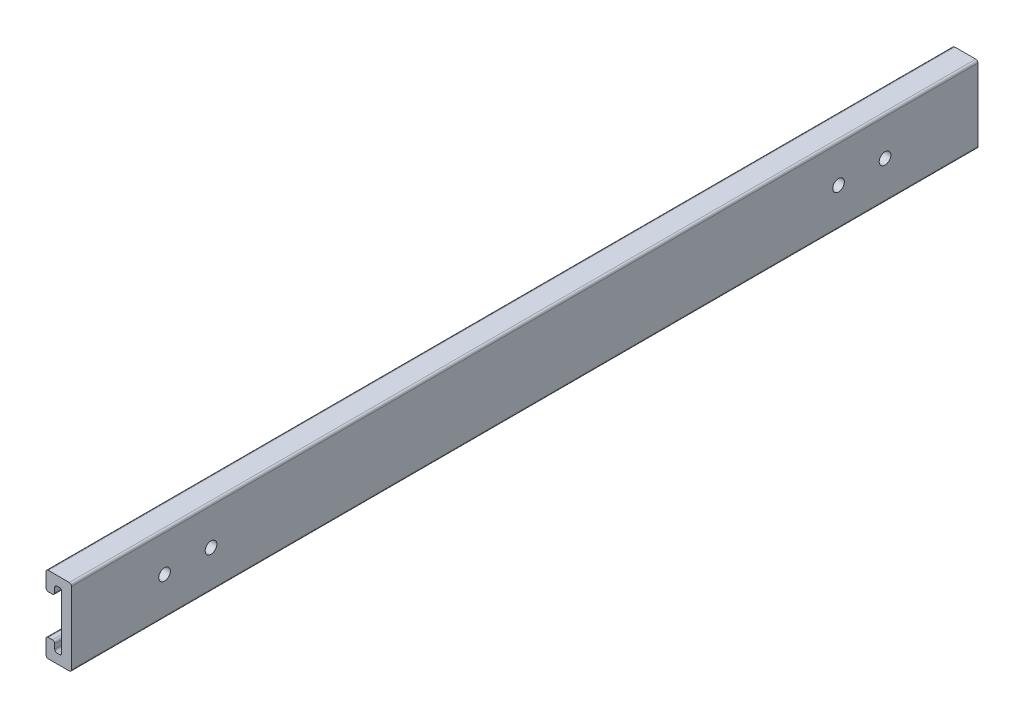
SolidWorks part; units mm, degrees
material "Brass"
ref_plane "Front Plane" through (0, 0, 0) normal (0, 0, 1) x (1, 0, 0)
ref_plane "Top Plane" through (0, 0, 0) normal (0, 1, 0) x (1, 0, 0)
ref_plane "Right Plane" through (0, 0, 0) normal (1, 0, 0) x (0, 0, -1)
sketch "Sketch1" plane through (0, 0, 0) normal (0, 0, 1) x (1, 0, 0)
  line L0 (5.5, 0) -> (-5.5, 0) construction
  line L1 (5.5, -15.5) -> (5.5, 15.5)
  line L2 (4.5, 16.5) -> (-4.5, 16.5)
  line L3 (-5.5, 15.5) -> (-5.5, 9.5)
  line L4 (-4.5, 8.5) -> (-2.75, 8.5)
  line L5 (-1.75, 9.5) -> (-1.75, 11.5)
  line L6 (-0.75, 12.5) -> (0.25, 12.5)
  line L7 (1.25, 11.5) -> (1.25, -11.5)
  line L8 (-0.75, -12.5) -> (0.25, -12.5)
  line L9 (-1.75, -9.5) -> (-1.75, -11.5)
  line L10 (-4.5, -8.5) -> (-2.75, -8.5)
  line L11 (-5.5, -15.5) -> (-5.5, -9.5)
  line L12 (4.5, -16.5) -> (-4.5, -16.5)
  arc A0 (5.5, 15.5) -> (4.5, 16.5) centre (4.5, 15.5) ccw
  arc A1 (-4.5, 16.5) -> (-5.5, 15.5) centre (-4.5, 15.5) ccw
  arc A2 (0.25, 12.5) -> (1.25, 11.5) centre (0.25, 11.5) cw
  arc A3 (-1.75, 11.5) -> (-0.75, 12.5) centre (-0.75, 11.5) cw
  arc A4 (-2.75, 8.5) -> (-1.75, 9.5) centre (-2.75, 9.5) ccw
  arc A5 (-5.5, 9.5) -> (-4.5, 8.5) centre (-4.5, 9.5) ccw
  arc A6 (-5.5, -9.5) -> (-4.5, -8.5) centre (-4.5, -9.5) cw
  arc A7 (-2.75, -8.5) -> (-1.75, -9.5) centre (-2.75, -9.5) cw
  arc A8 (-1.75, -11.5) -> (-0.75, -12.5) centre (-0.75, -11.5) ccw
  arc A9 (0.25, -12.5) -> (1.25, -11.5) centre (0.25, -11.5) ccw
  arc A10 (-4.5, -16.5) -> (-5.5, -15.5) centre (-4.5, -15.5) cw
  arc A11 (5.5, -15.5) -> (4.5, -16.5) centre (4.5, -15.5) cw
  point P4 (0, 0)
  point P11 (-5.5, -8.5)
  point P13 (5.5, 16.5)
  point P16 (-5.5, 16.5)
  point P19 (1.25, 12.5)
  point P22 (-1.75, 12.5)
  point P27 (-5.5, 8.5)
  point P46 (1.25, 0)
  point P47 (-1.75, -12.5)
  point P48 (1.25, -12.5)
  point P49 (-5.5, -16.5)
  point P50 (5.5, -16.5)
  dimension "D8" = 1
  dimension "D1" = 11
  dimension "D2" = 11
  dimension "D3" = 8
  dimension "D4" = 12.5
  dimension "D5" = 16.5
  dimension "D6" = 4.25
  dimension "D7" = 3
extrude "Boss-Extrude1" add sketch "Sketch1" along normal mid plane 390
sketch "Sketch2" plane through (1.25, 0, 0) normal (-1, 0, 0) x (0, 0, 1)
  line L0 (-195, 0) -> (195, 0) construction
  line L1 (195, 11.5) -> (195, -11.5) construction
  line L2 (0, 0) -> (0, 16.5) construction
  line L3 (195, 16.5) -> (-195, 16.5) construction
  circle A0 centre (155, 0) radius 2.5
  circle A1 centre (135, 0) radius 2.5
  circle A2 centre (-135, 0) radius 2.5
  circle A3 centre (-155, 0) radius 2.5
  point P6 (0, 0)
  dimension "D3" = 5
  dimension "D1" = 40
  dimension "D2" = 20
extrude "Cut-Extrude1" cut sketch "Sketch2" against normal up to next
